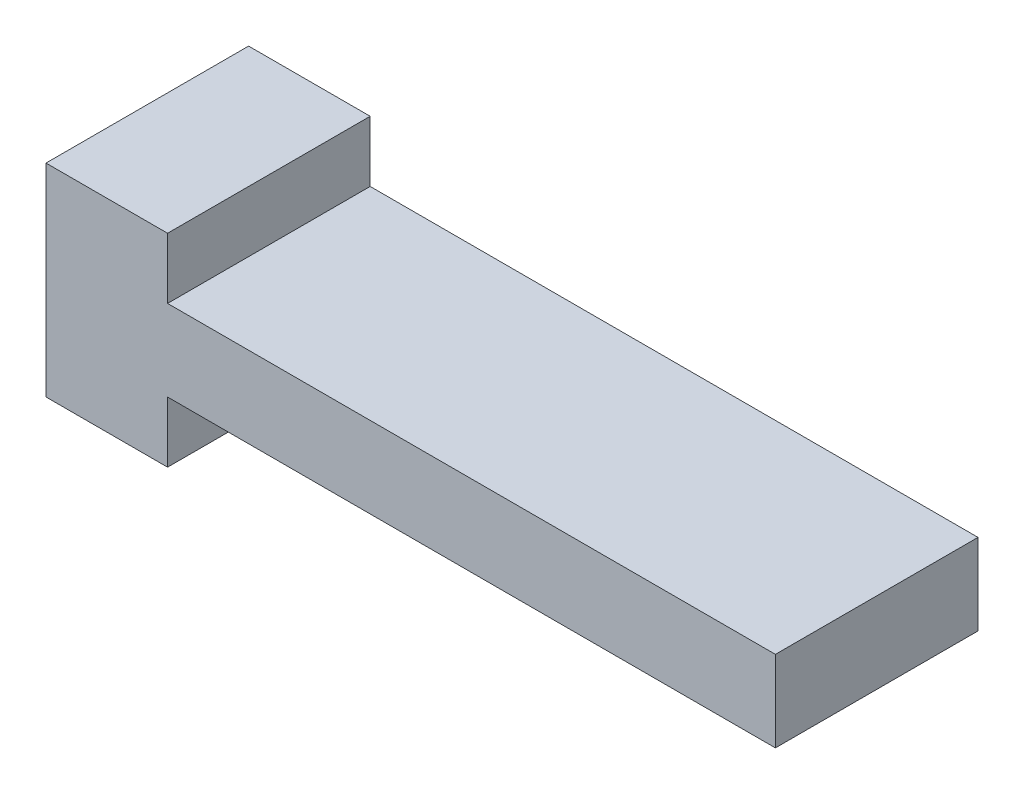
SolidWorks part; units mm, degrees
ref_plane "Front Plane" through (0, 0, 0) normal (0, 0, 1) x (1, 0, 0)
ref_plane "Top Plane" through (0, 0, 0) normal (0, 1, 0) x (1, 0, 0)
ref_plane "Right Plane" through (0, 0, 0) normal (1, 0, 0) x (0, 0, -1)
sketch "Sketch1" plane through (0, 0, 0) normal (0, 0, 1) x (1, 0, 0)
  line L0 (0, 25) -> (0, -25)
  line L1 (0, -25) -> (30, -25)
  line L2 (30, -25) -> (30, -10)
  line L3 (30, -10) -> (180, -10)
  line L4 (180, -10) -> (180, 10)
  line L5 (180, 10) -> (30, 10)
  line L6 (30, 10) -> (30, 25)
  line L7 (30, 25) -> (0, 25)
  line L8 (30, 10) -> (30, -10) construction
  point P3 (0, 0)
  point P10 (180, 0)
  dimension "D1" = 30
  dimension "D2" = 20
  dimension "D3" = 150
  dimension "D4" = 50
extrude "Boss-Extrude1" add sketch "Sketch1" along normal blind 50
